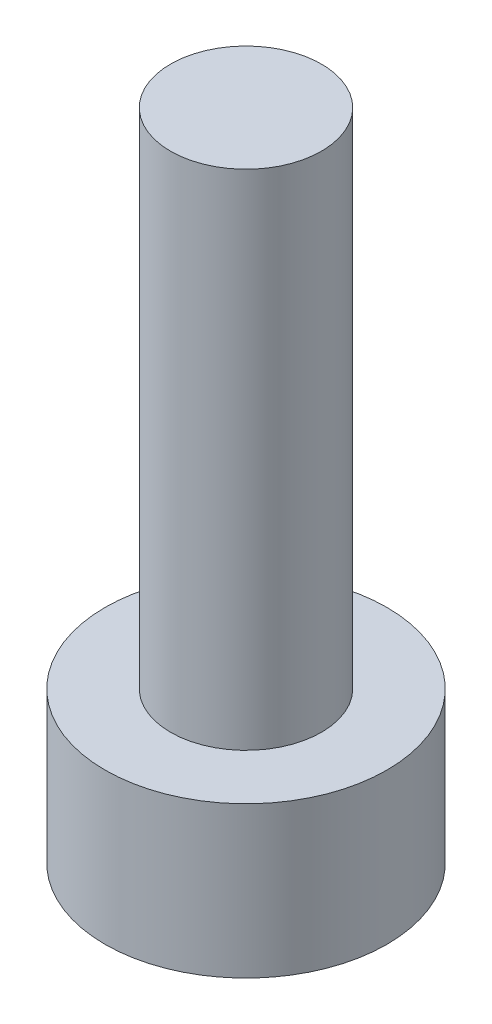
SolidWorks part; units mm, degrees
ref_plane "前视基准面" through (0, 0, 0) normal (0, 0, 1) x (1, 0, 0)
ref_plane "上视基准面" through (0, 0, 0) normal (0, 1, 0) x (1, 0, 0)
ref_plane "右视基准面" through (0, 0, 0) normal (1, 0, 0) x (0, 0, -1)
other "Configuration Table"
sketch "草图1" plane through (0, 0, 0) normal (0, 1, 0) x (1, 0, 0)
  circle A0 centre (0, 0) radius 2.8
  dimension "D1" = 5.6
extrude "凸台-拉伸1" add sketch "草图1" along normal blind 3
sketch "草图2" plane through (0, 3, 0) normal (0, 1, 0) x (1, 0, 0)
  circle A0 centre (0, 0) radius 1.5
  dimension "D1" = 3
extrude "凸台-拉伸2" add sketch "草图2" along normal blind 10
cosmetic thread "装饰螺纹线1" parameters "D2"=2
sketch "草图3" plane through (0, 0, 0) normal (0, -1, 0) x (1, 0, 0)
  line L1 (1.0846, -0.9524) -> (1.3671, 0.4631)
  line L2 (1.3671, 0.4631) -> (0.2825, 1.4155)
  line L3 (0.2825, 1.4155) -> (-1.0846, 0.9524)
  line L4 (-1.0846, 0.9524) -> (-1.3671, -0.4631)
  line L5 (-1.3671, -0.4631) -> (-0.2825, -1.4155)
  line L6 (-0.2825, -1.4155) -> (1.0846, -0.9524)
  circle A0 centre (0, 0) radius 1.25 construction
  dimension "D1" = 2.5
extrude "切除-拉伸1" cut sketch "草图3" against normal blind 1.5
